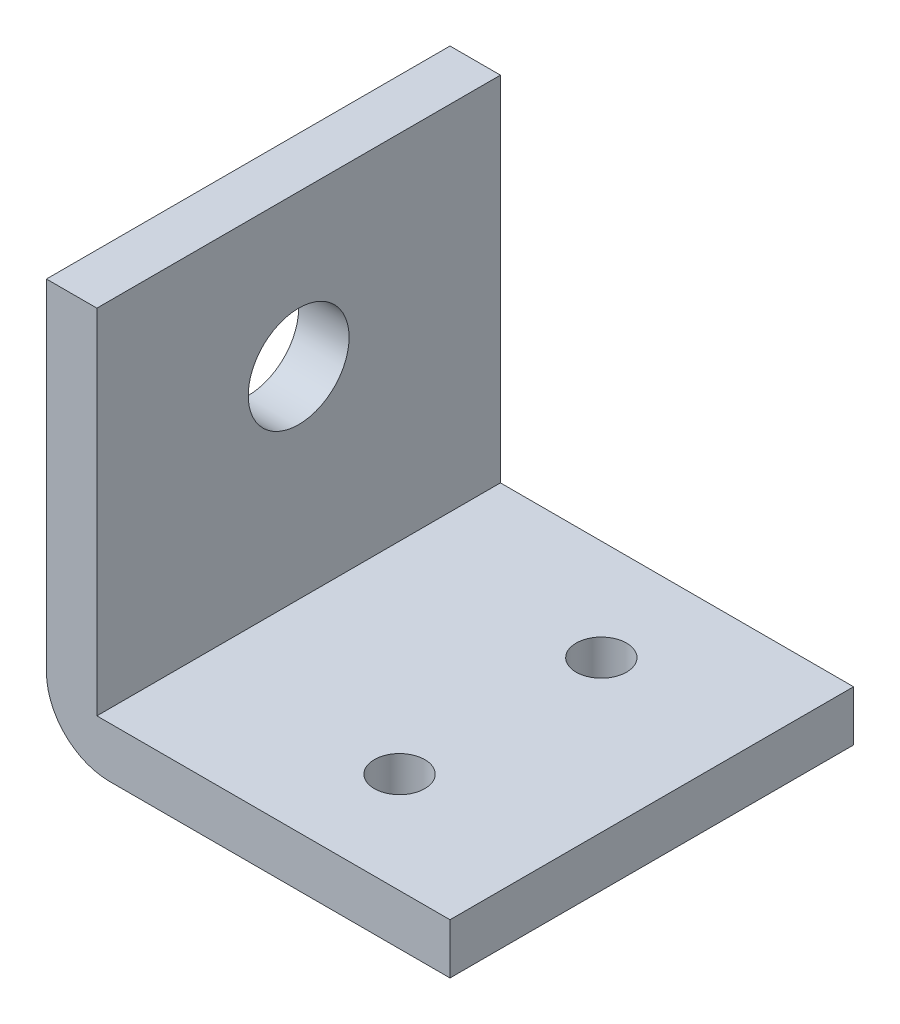
SolidWorks part; units mm, degrees
ref_plane "Front Plane" through (0, 0, 0) normal (0, 0, 1) x (1, 0, 0)
ref_plane "Top Plane" through (0, 0, 0) normal (0, 1, 0) x (1, 0, 0)
ref_plane "Right Plane" through (0, 0, 0) normal (1, 0, 0) x (0, 0, -1)
sketch "Sketch1" plane through (0, 0, 0) normal (0, 0, 1) x (1, 0, 0)
  line L0 (0, 40) -> (0, 6.25)
  line L1 (6.25, 0) -> (40, 0)
  line L2 (5, 40) -> (5, 5)
  line L3 (5, 5) -> (40, 5)
  line L4 (0, 40) -> (5, 40)
  line L5 (40, 0) -> (40, 5)
  line L6 (0, 0) -> (40, 0) construction
  line L7 (0, 40) -> (0, 0) construction
  arc A0 (6.25, 0) -> (0, 6.25) centre (6.25, 6.25) cw
  point P10 (0, 0)
  dimension "D4" = 6.25
  dimension "D1" = 40
  dimension "D2" = 40
  dimension "D3" = 5
extrude "Boss-Extrude3" add sketch "Sketch1" along normal mid plane 40
sketch "Sketch4" plane through (0, 5, 0) normal (0, 1, 0) x (1, 0, 0)
  line L0 (40, 20) -> (5, 20) construction
  line L1 (40, -20) -> (5, -20) construction
  line L2 (40, -20) -> (40, 20) construction
  circle A0 centre (25, -10) radius 2.5
  circle A1 centre (25, 10) radius 2.5
  point P0 (25, 10)
  point P1 (25, -10)
  dimension "D5" = 5
  dimension "D6" = 5
  dimension "D1" = 20
  dimension "D2" = 10
  dimension "D3" = 10
  dimension "D4" = 15
extrude "Cut-Extrude2" cut sketch "Sketch4" against normal blind 40 contours A0 | A1
sketch "Sketch5" plane through (5, 0, 0) normal (1, 0, 0) x (0, 0, -1)
  line L0 (20, 5) -> (20, 40) construction
  line L1 (-20, 40) -> (20, 40) construction
  line L2 (-20, 0) -> (20, 0) construction
  circle A0 centre (0, 25) radius 5
  dimension "D2" = 10
  dimension "D1" = 15
  dimension "D3" = 20
  dimension "D4" = 40
extrude "Cut-Extrude3" cut sketch "Sketch5" against normal blind 40
